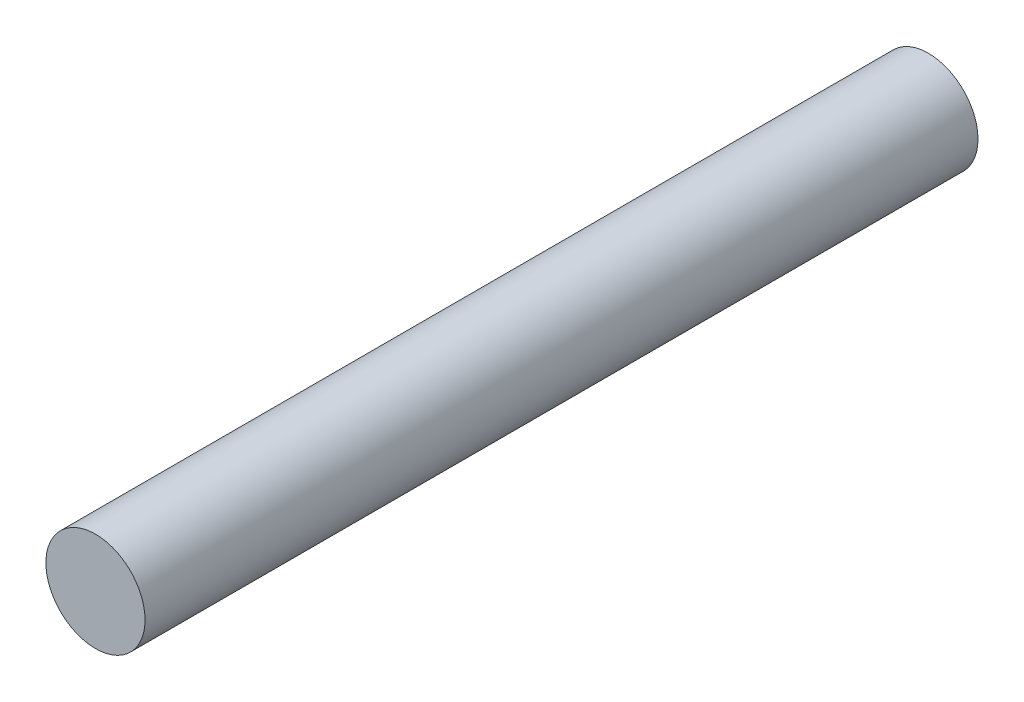
SolidWorks part; units mm, degrees
ref_plane "Front Plane" through (0, 0, 0) normal (0, 0, 1) x (1, 0, 0)
ref_plane "Top Plane" through (0, 0, 0) normal (0, 1, 0) x (1, 0, 0)
ref_plane "Right Plane" through (0, 0, 0) normal (1, 0, 0) x (0, 0, -1)
sketch "Sketch1" plane through (0, 0, 0) normal (0, 0, 1) x (1, 0, 0)
  circle A0 centre (0, 0) radius 1.5
  dimension "D1" = 3
extrude "Boss-Extrude1" add sketch "Sketch1" along normal blind 25.2
